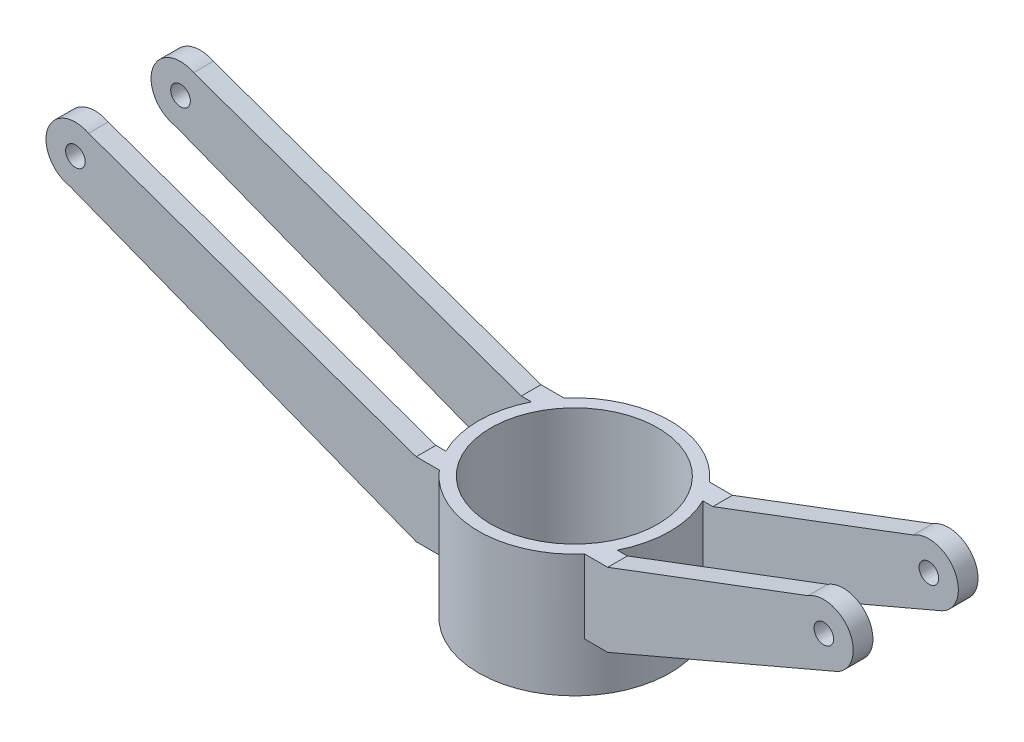
SolidWorks part; units mm, degrees
ref_plane "Front Plane" through (0, 0, 0) normal (0, 0, 1) x (1, 0, 0)
ref_plane "Top Plane" through (0, 0, 0) normal (0, 1, 0) x (1, 0, 0)
ref_plane "Right Plane" through (0, 0, 0) normal (1, 0, 0) x (0, 0, -1)
sketch "Sketch2" plane through (0, 0, 0) normal (0, 1, 0) x (1, 0, 0)
  circle A0 centre (0, 0) radius 39
  circle A1 centre (0, 0) radius 34
  dimension "D1" = 78
  dimension "D2" = 5
extrude "Boss-Extrude1" add sketch "Sketch2" along normal blind 50
ref_plane "Plane1" through (0, 0, 25.4) normal (0, 0, 1) x (1, 0, 0)
sketch "Sketch3" plane through (0, 0, 25.4) normal (0, 0, 1) x (1, 0, 0)
  line L0 (-39, 20) -> (-39, 50)
  line L2 (39, 50) -> (39, 20)
  line L4 (-39, 35) -> (-177.7927, 86.6165) construction
  line L5 (-39, 20) -> (-179.9913, 74.8197)
  line L6 (-39, 50) -> (-172.4309, 97.3521)
  line L7 (39, 35) -> (126.9958, 70.642) construction
  line L8 (39, 50) -> (120.5579, 80.7688)
  line L9 (39, 20) -> (130.9179, 59.301)
  circle A0 centre (-177.7927, 86.6165) radius 4
  arc A1 (-172.4309, 97.3521) -> (-179.9913, 74.8197) centre (-177.7927, 86.6165) ccw
  circle A2 centre (126.9958, 70.642) radius 4
  arc A3 (130.9179, 59.301) -> (120.5579, 80.7688) centre (126.9958, 70.642) ccw
  point P4 (-39, 20)
  point P9 (-39, 35)
  point P13 (39, 20)
  point P16 (39, 35)
  dimension "D5" = 8
  dimension "D6" = 24
  dimension "D11" = 8
  dimension "D12" = 24
  dimension "D1" = 30
  dimension "D2" = 15
  dimension "D3" = 69.6
  dimension "D4" = 148.08
  dimension "D7" = 30
  dimension "D8" = 15
  dimension "D9" = 67.95
  dimension "D10" = 94.94
extrude "Boss-Extrude2" add sketch "Sketch3" against normal blind 8 separate body
ref_plane "Plane2" through (0, 0, -25.4) normal (0, 0, 1) x (1, 0, 0)
sketch "Sketch4" plane through (0, 0, -25.4) normal (0, 0, 1) x (1, 0, 0)
  line L0 (39, 50) -> (120.5579, 80.7688) construction
  line L1 (130.9179, 59.301) -> (39, 20) construction
  line L2 (39, 20) -> (39, 50) construction
  line L3 (-172.4309, 97.3521) -> (-39, 50) construction
  line L4 (-39, 50) -> (-39, 20) construction
  line L5 (-39, 20) -> (-179.9913, 74.8197) construction
  line L6 (39, 50) -> (120.5579, 80.7688)
  line L7 (130.9179, 59.301) -> (39, 20)
  line L8 (39, 20) -> (39, 50)
  line L9 (-172.4309, 97.3521) -> (-39, 50)
  line L10 (-39, 50) -> (-39, 20)
  line L11 (-39, 20) -> (-179.9913, 74.8197)
  arc A0 (130.9179, 59.301) -> (120.5579, 80.7688) centre (126.9958, 70.642) ccw construction
  arc A1 (-172.4309, 97.3521) -> (-179.9913, 74.8197) centre (-177.7927, 86.6165) ccw construction
  arc A2 (130.9179, 59.301) -> (120.5579, 80.7688) centre (126.9958, 70.642) ccw
  arc A3 (-172.4309, 97.3521) -> (-179.9913, 74.8197) centre (-177.7927, 86.6165) ccw
  circle A4 centre (126.9958, 70.642) radius 4 construction
  circle A5 centre (-177.7927, 86.6165) radius 4 construction
  circle A6 centre (126.9958, 70.642) radius 4
  circle A7 centre (-177.7927, 86.6165) radius 4
extrude "Boss-Extrude3" add sketch "Sketch4" along normal blind 8 separate body
sketch "Sketch6" plane through (0, 50, 0) normal (0, 1, 0) x (1, 0, 0)
  line L1 (39, 25.4) -> (39, 17.4) construction
  line L7 (39, -17.4) -> (39, -25.4) construction
  line L9 (-39, -25.4) -> (-39, -17.4) construction
  line L15 (-39, 17.4) -> (-39, 25.4) construction
  line L17 (39, 25.4) -> (39, 17.4)
  line L23 (39, -17.4) -> (39, -25.4)
  line L25 (-39, -25.4) -> (-39, -17.4)
  line L31 (-39, 17.4) -> (-39, 25.4)
  line L32 (-39, 25.4) -> (-29.5946, 25.4)
  line L33 (-39, 17.4) -> (-34.9033, 17.4)
  line L34 (-39, -17.4) -> (-34.9033, -17.4)
  line L35 (-39, -25.4) -> (-29.5946, -25.4)
  line L36 (39, 25.4) -> (29.5946, 25.4)
  line L37 (39, 17.4) -> (34.9033, 17.4)
  line L38 (39, -17.4) -> (34.9033, -17.4)
  line L39 (39, -25.4) -> (29.5946, -25.4)
  arc A0 (-29.5946, 25.4) -> (-34.9033, 17.4) centre (0, 0) ccw
  circle A1 centre (0, 0) radius 39
  arc A2 (-34.9033, -17.4) -> (-29.5946, -25.4) centre (0, 0) ccw
  arc A3 (29.5946, -25.4) -> (34.9033, -17.4) centre (0, 0) ccw
  arc A4 (34.9033, 17.4) -> (29.5946, 25.4) centre (0, 0) ccw
  dimension "D1" = 0
extrude "Boss-Extrude4" add sketch "Sketch6" against normal blind 30
